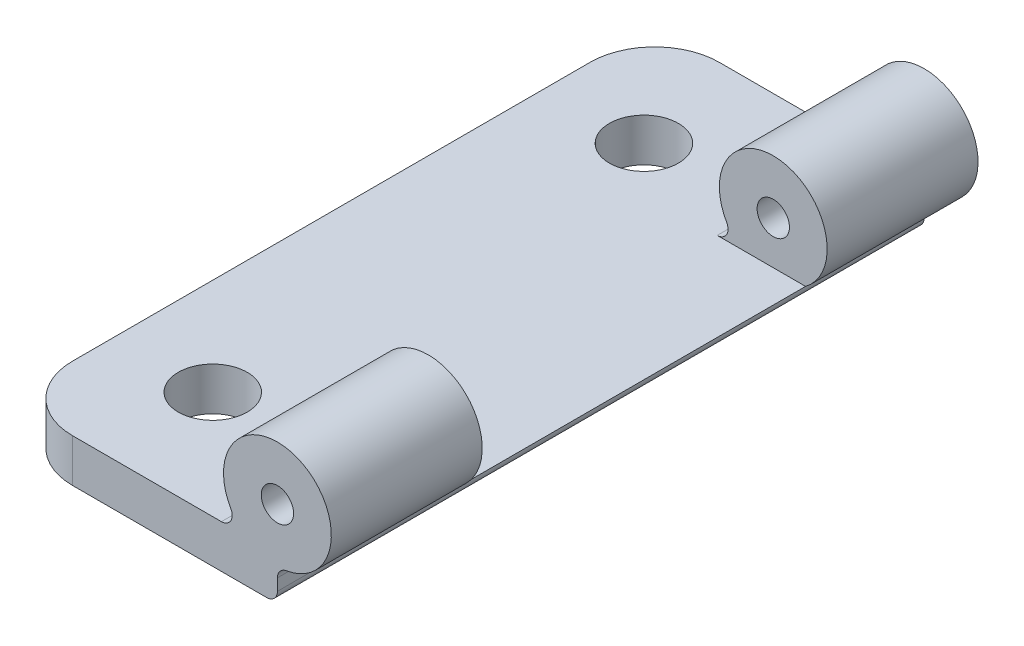
SolidWorks part; units mm, degrees
ref_plane "前视基准面" through (0, 0, 0) normal (0, 0, 1) x (1, 0, 0)
ref_plane "上视基准面" through (0, 0, 0) normal (0, 1, 0) x (1, 0, 0)
ref_plane "右视基准面" through (0, 0, 0) normal (1, 0, 0) x (0, 0, -1)
other "Configuration Table"
sketch "草图1" plane through (0, 0, 0) normal (0, 1, 0) x (1, 0, 0)
  line L1 (3, 0) -> (12.5, 0)
  line L2 (0, -3) -> (0, -27)
  line L3 (3, -30) -> (12.5, -30)
  line L4 (12.5, 0) -> (12.5, -30)
  circle A0 centre (4.5, -5) radius 1.6
  circle A1 centre (4.5, -25) radius 1.6
  arc A2 (0, -27) -> (3, -30) centre (3, -27) ccw
  arc A3 (3, 0) -> (0, -3) centre (3, -3) ccw
  point P9 (12.5, -15)
  point P12 (0, -30)
  point P15 (0, 0)
  dimension "D3" = 3.2
  dimension "D4" = 3.2
  dimension "D9" = 3
  dimension "D1" = 12.5
  dimension "D2" = 30
  dimension "D5" = 8
  dimension "D6" = 8
  dimension "D7" = 10
  dimension "D8" = 10
extrude "凸台-拉伸1" add sketch "草图1" along normal blind 2
sketch "草图2" plane through (0, 0, 30) normal (0, 0, 1) x (1, 0, 0)
  line L0 (12.5, 2) -> (12.5, 0) construction
  line L1 (3, 0) -> (12.5, 0) construction
  circle A0 centre (12.5, 4) radius 2.5
  dimension "D1" = 5
  dimension "D2" = 4
extrude "凸台-拉伸2" add sketch "草图2" against normal up to surface (30 mm away) contours A0 up to face at (7.75, 1, 0)
fillet "圆角1" radius 0.5 3 edges at (11, 2, 15) (12.5, 0, 15) (12.5, 1.5, 15)
sketch "草图3" plane through (0, 0, 30) normal (0, 0, 1) x (1, 0, 0)
  circle A0 centre (12.5, 4) radius 0.75
  dimension "D1" = 1.5
extrude "切除-拉伸1" cut sketch "草图3" against normal through all
sketch "草图4" plane through (0, 2, 0) normal (0, 1, 0) x (1, 0, 0)
  line L8 (9.9019, -30) -> (9.9019, 0) construction
  line L9 (9.9019, -7) -> (15, -7)
  line L10 (9.9019, -7) -> (9.9019, -23)
  line L11 (9.9019, -23) -> (15, -23)
  line L12 (15, -7) -> (15, -23)
  line L13 (15, -30) -> (15, 0) construction
  line L14 (3, -30) -> (9.9019, -30) construction
  line L15 (15, 0) -> (10, 0) construction
  dimension "D1" = 7
  dimension "D2" = 7
extrude "切除-拉伸2" cut sketch "草图4" along normal through all
